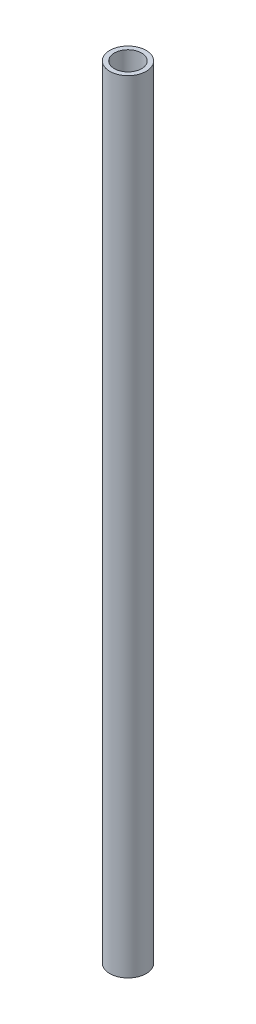
SolidWorks part; units mm, degrees
ref_plane "Front Plane" through (0, 0, 0) normal (0, 0, 1) x (1, 0, 0)
ref_plane "Top Plane" through (0, 0, 0) normal (0, 1, 0) x (1, 0, 0)
ref_plane "Right Plane" through (0, 0, 0) normal (1, 0, 0) x (0, 0, -1)
sketch "Sketch1" plane through (0, 0, 0) normal (0, 1, 0) x (1, 0, 0)
  circle A0 centre (-391.1817, 212.7433) radius 12.7
  circle A1 centre (-391.1817, 212.7433) radius 9.525
  dimension "D1" = 19.05
  dimension "D2" = 25.4
extrude "Boss-Extrude2" add sketch "Sketch1" along normal blind 546.1
